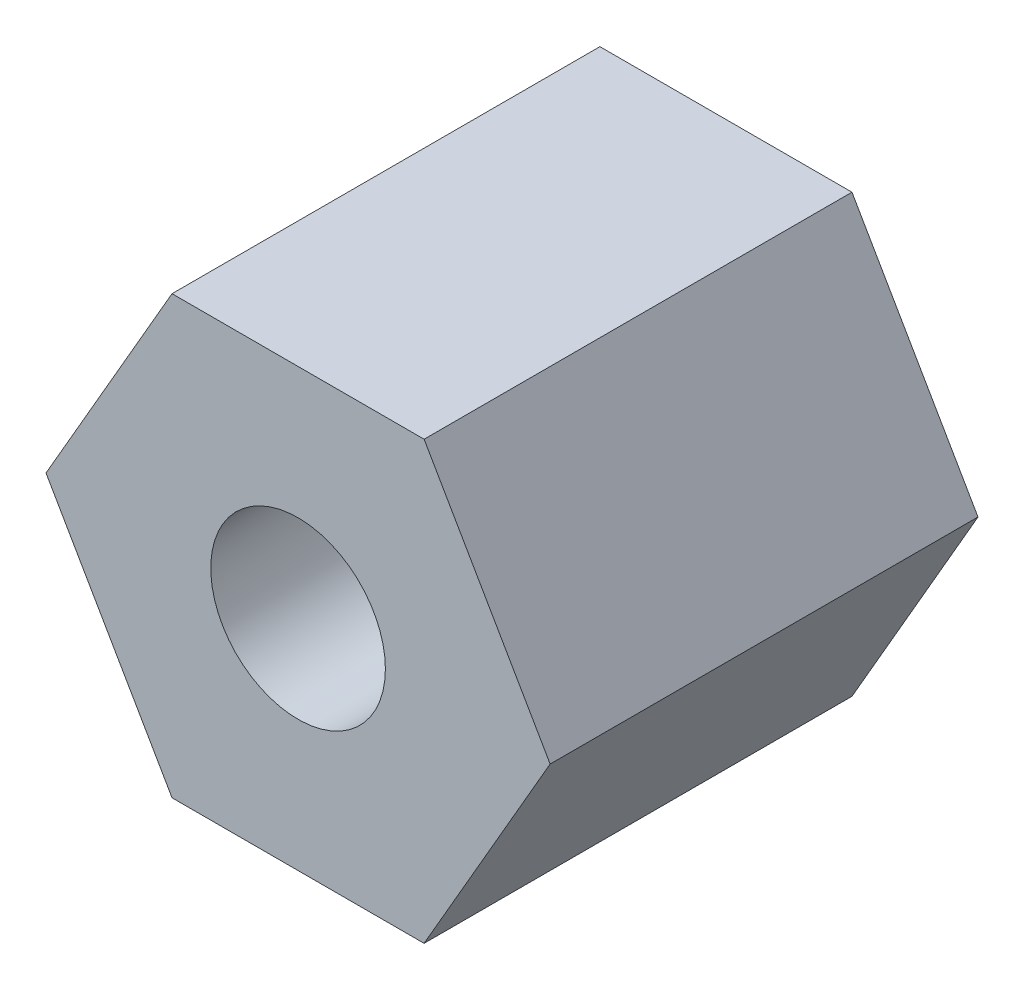
SolidWorks part; units mm, degrees
ref_plane "前视基准面" through (0, 0, 0) normal (0, 0, 1) x (1, 0, 0)
ref_plane "上视基准面" through (0, 0, 0) normal (0, 1, 0) x (1, 0, 0)
ref_plane "右视基准面" through (0, 0, 0) normal (1, 0, 0) x (0, 0, -1)
sketch "草图1" plane through (0, 0, 0) normal (0, 0, 1) x (1, 0, 0)
  line L1 (2.8868, -5) -> (5.7735, 0)
  line L2 (5.7735, 0) -> (2.8868, 5)
  line L3 (2.8868, 5) -> (-2.8868, 5)
  line L4 (-2.8868, 5) -> (-5.7735, 0)
  line L5 (-5.7735, 0) -> (-2.8868, -5)
  line L6 (-2.8868, -5) -> (2.8868, -5)
  circle A0 centre (0, 0) radius 2
  circle A1 centre (0, 0) radius 5 construction
  dimension "D1" = 10
  dimension "D2" = 4
extrude "凸台-拉伸1" add sketch "草图1" along normal blind 9.8
